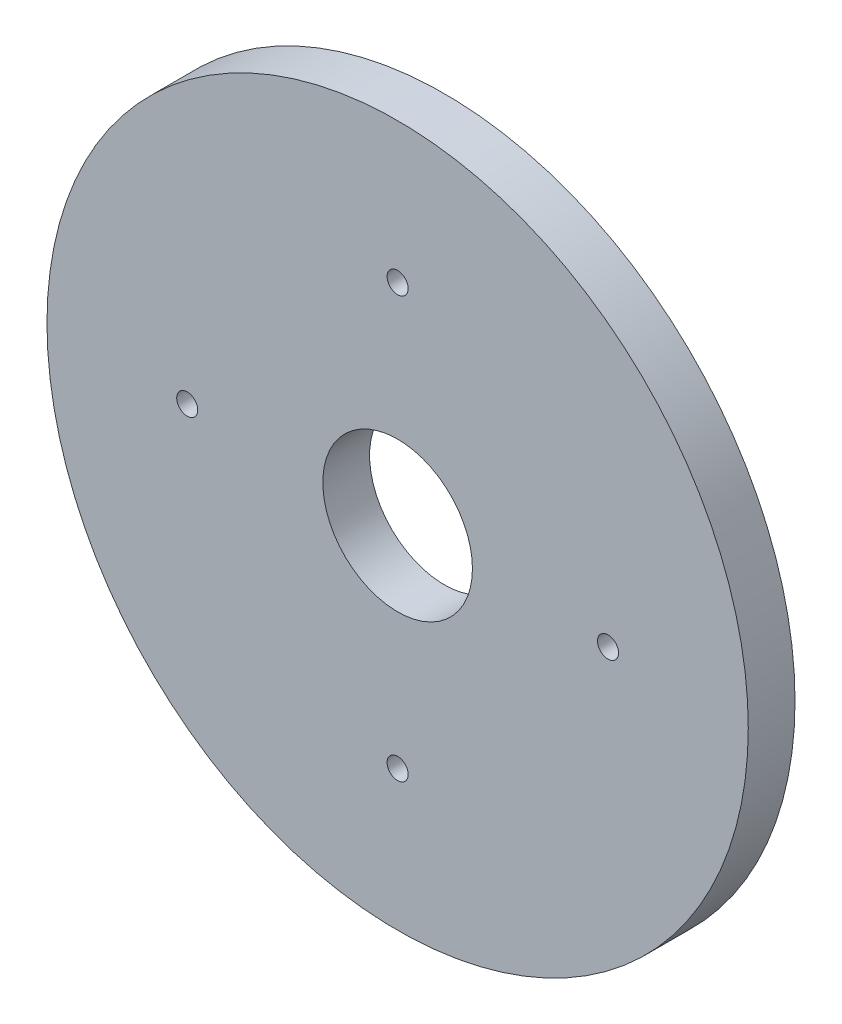
SolidWorks part; units mm, degrees
ref_plane "Front Plane" through (0, 0, 0) normal (0, 0, 1) x (1, 0, 0)
ref_plane "Top Plane" through (0, 0, 0) normal (0, 1, 0) x (1, 0, 0)
ref_plane "Right Plane" through (0, 0, 0) normal (1, 0, 0) x (0, 0, -1)
ref_plane "Plane1" through (0, 0, 113) normal (0, 0, 1) x (1, 0, 0)
sketch "Sketch1" plane through (0, 0, 113) normal (0, 0, 1) x (1, 0, 0)
  circle A0 centre (300, 300) radius 75
extrude "Boss-Extrude1" add sketch "Sketch1" along normal blind 10
sketch "Sketch2" plane through (0, 0, 123) normal (0, 0, 1) x (1, 0, 0)
  circle A0 centre (300, 300) radius 16
extrude "Cut-Extrude1" cut sketch "Sketch2" against normal blind 30
sketch "Sketch3" plane through (0, 0, 123) normal (0, 0, 1) x (1, 0, 0)
  circle A0 centre (345, 300) radius 2.25
extrude "Cut-Extrude2" cut sketch "Sketch3" against normal blind 30
sketch "Sketch4" plane through (0, 0, 123) normal (0, 0, 1) x (1, 0, 0)
  circle A0 centre (255, 300) radius 2.25
extrude "Cut-Extrude3" cut sketch "Sketch4" against normal blind 30
sketch "Sketch5" plane through (0, 0, 123) normal (0, 0, 1) x (1, 0, 0)
  circle A0 centre (300, 345) radius 2.25
extrude "Cut-Extrude4" cut sketch "Sketch5" against normal blind 30
sketch "Sketch6" plane through (0, 0, 123) normal (0, 0, 1) x (1, 0, 0)
  circle A0 centre (300, 255) radius 2.25
extrude "Cut-Extrude5" cut sketch "Sketch6" against normal blind 30
